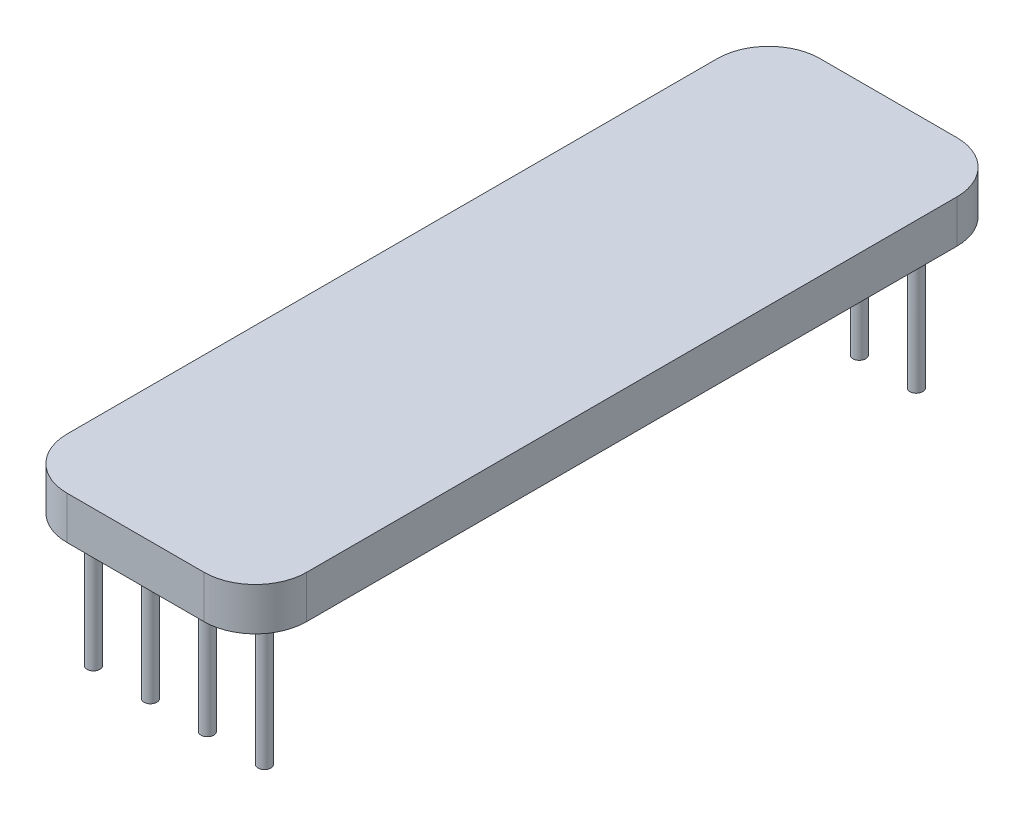
SolidWorks part; units mm, degrees
ref_plane "Front Plane" through (0, 0, 0) normal (0, 0, 1) x (1, 0, 0)
ref_plane "Top Plane" through (0, 0, 0) normal (0, 1, 0) x (1, 0, 0)
ref_plane "Right Plane" through (0, 0, 0) normal (1, 0, 0) x (0, 0, -1)
sketch "Sketch2" plane through (0, 0, 0) normal (0, 1, 0) x (1, 0, 0)
  line L1 (-4, 22) -> (4, 22)
  line L2 (-7, 19) -> (-7, -19)
  line L3 (-4, -22) -> (4, -22)
  line L4 (7, 19) -> (7, -19)
  line L5 (-7, 22) -> (7, -22) construction
  line L6 (-7, -22) -> (7, 22) construction
  arc A0 (7, 19) -> (4, 22) centre (4, 19) ccw
  arc A1 (-4, 22) -> (-7, 19) centre (-4, 19) ccw
  arc A2 (-7, -19) -> (-4, -22) centre (-4, -19) ccw
  arc A3 (4, -22) -> (7, -19) centre (4, -19) ccw
  point P0 (0, 0)
  dimension "D3" = 3
  dimension "D1" = 14
  dimension "D2" = 44
extrude "Boss-Extrude1" add sketch "Sketch2" along normal blind 2.5
sketch "Sketch3" plane through (0, 2.5, 0) normal (0, 1, 0) x (1, 0, 0)
  line L0 (0, -22) -> (0, 22) construction
  line L1 (-4, -22) -> (4, -22) construction
  line L2 (4, 22) -> (-4, 22) construction
  line L3 (-7, 0) -> (7, 0) construction
  line L4 (-7, 19) -> (-7, -19) construction
  line L5 (7, -19) -> (7, 19) construction
  line L7 (-6.5, -11) -> (6.5, -11)
  line L8 (-6.5, -11) -> (-6.5, -21)
  line L9 (-6.5, -21) -> (6.5, -21)
  line L10 (6.5, -11) -> (6.5, -21)
  line L11 (-6.5, -11) -> (6.5, -21) construction
  line L12 (-6.5, -21) -> (6.5, -11) construction
  point P12 (0, -16)
  dimension "D1" = 1
  dimension "D2" = 0.5
  dimension "D3" = 10
extrude "Boss-Extrude2" [suppressed] add sketch "Sketch3" along normal blind 8
sketch "Sketch4" plane through (0, 0, 0) normal (0, -1, 0) x (1, 0, 0)
  line L0 (7, 19.46) -> (-7, 19.46) construction
  line L1 (7, 19) -> (7, -19) construction
  line L2 (-7, -19) -> (-7, 19) construction
  line L3 (-4, 22) -> (4, 22) construction
  circle A0 centre (-5, 19.46) radius 0.375
  circle A1 centre (-1.67, 19.46) radius 0.375
  circle A2 centre (1.66, 19.46) radius 0.375
  circle A3 centre (4.99, 19.46) radius 0.375
  dimension "D2" = 0.75
  dimension "D3" = 2
  dimension "D5" = 5.33
  dimension "D1" = 2.54
  dimension "D4" = 4
extrude "Boss-Extrude3" add sketch "Sketch4" along normal blind 8
pattern_linear "LPattern1" count 2 spacing 38.1 along (0, 0, -1) of "Boss-Extrude3"
